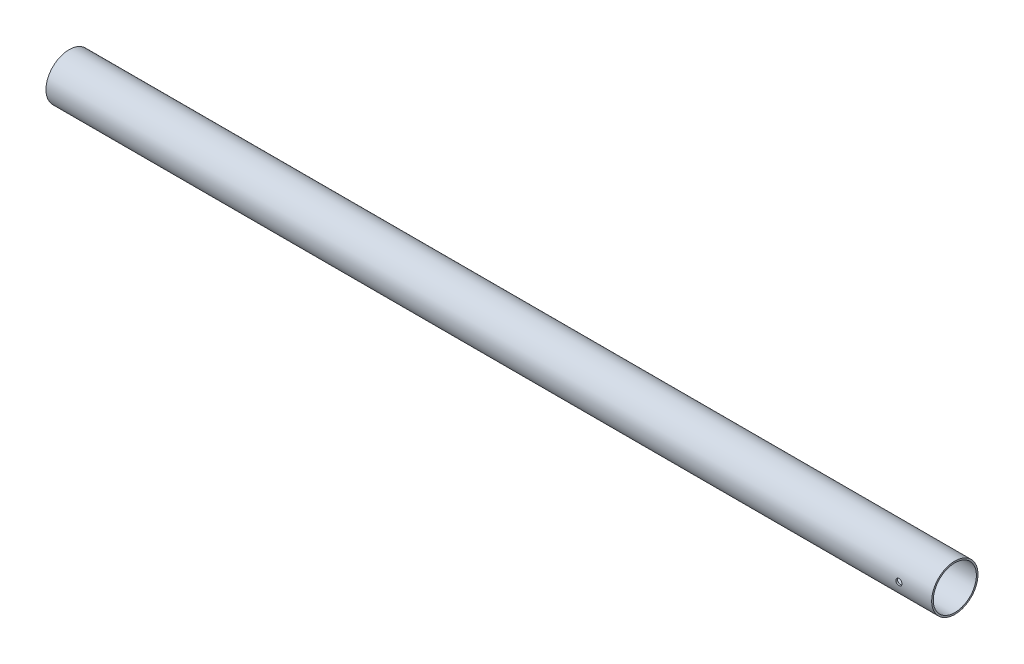
SolidWorks part; units mm, degrees
ref_plane "Front Plane" through (0, 0, 0) normal (0, 0, 1) x (1, 0, 0)
ref_plane "Top Plane" through (0, 0, 0) normal (0, 1, 0) x (1, 0, 0)
ref_plane "Right Plane" through (0, 0, 0) normal (1, 0, 0) x (0, 0, -1)
sketch "Sketch1" plane through (0, 0, 0) normal (1, 0, 0) x (0, 0, -1)
  circle A0 centre (0, 0) radius 12.7
  circle A1 centre (0, 0) radius 11.811
extrude "Boss-Extrude1" add sketch "Sketch1" along normal blind 485.9
sketch "Sketch2" plane through (0, 0, 0) normal (0, 0, 1) x (1, 0, 0)
  circle A0 centre (467.9, 0) radius 1.7
extrude "Cut-Extrude1" cut sketch "Sketch2" against normal through all and the other way through all
